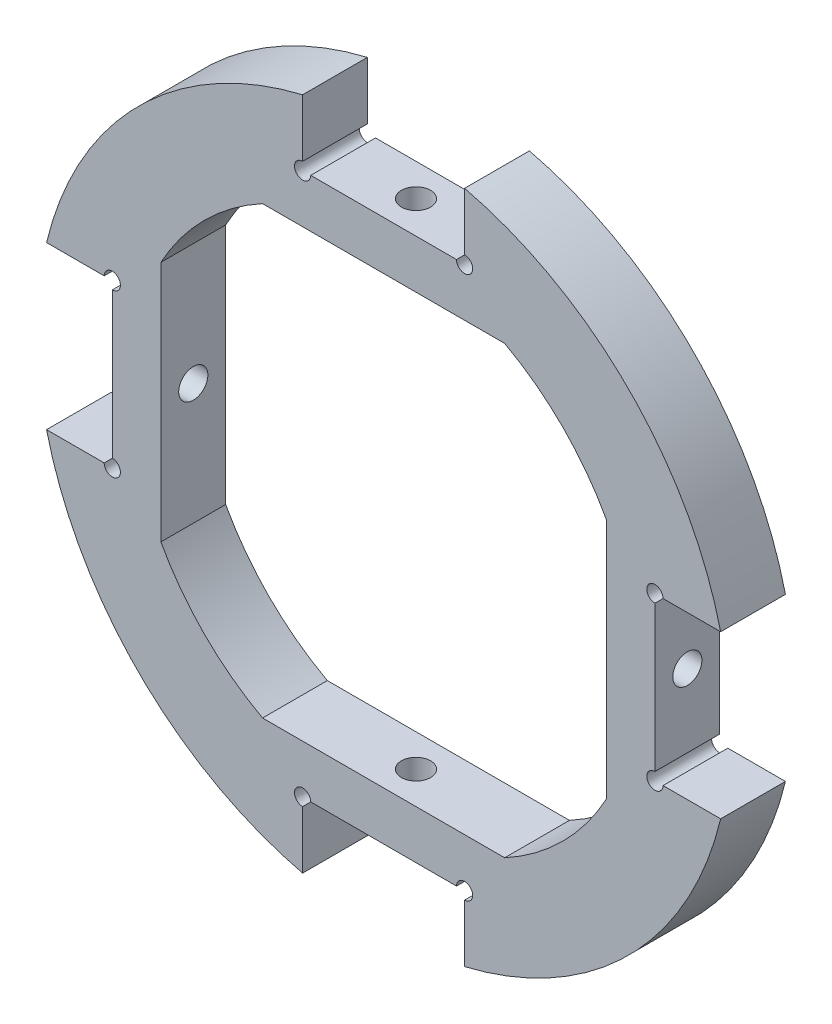
SolidWorks part; units mm, degrees
ref_plane "前视基准面" through (0, 0, 0) normal (0, 0, 1) x (1, 0, 0)
ref_plane "上视基准面" through (0, 0, 0) normal (0, 1, 0) x (1, 0, 0)
ref_plane "右视基准面" through (0, 0, 0) normal (1, 0, 0) x (0, 0, -1)
sketch "草图1" plane through (0, 0, 0) normal (0, 0, 1) x (1, 0, 0)
  line L0 (-24.4, 0) -> (24.4, 0) construction
  line L1 (-7.474, -13.75) -> (7.474, -13.75)
  line L2 (-7.474, 13.75) -> (7.474, 13.75)
  line L3 (13.75, 7.474) -> (13.75, -7.474)
  line L4 (-13.75, 7.474) -> (-13.75, -7.474)
  line L5 (-4.5, 16.75) -> (4.5, 16.75)
  line L6 (5, 20.8077) -> (5, 17.25)
  line L7 (-5, 20.8077) -> (-5, 17.25)
  line L8 (-16.75, -4.5) -> (-16.75, 4.5)
  line L9 (-20.8077, 5) -> (-17.25, 5)
  line L10 (-20.8077, -5) -> (-17.25, -5)
  line L11 (4.5, -16.75) -> (-4.5, -16.75)
  line L12 (-5, -20.8077) -> (-5, -17.25)
  line L13 (5, -20.8077) -> (5, -17.25)
  line L14 (16.75, 4.5) -> (16.75, -4.5)
  line L15 (20.8077, -5) -> (17.25, -5)
  line L16 (20.8077, 5) -> (17.25, 5)
  arc A0 (-7.474, 13.75) -> (-13.75, 7.474) centre (0, 0) ccw
  arc A1 (-13.75, -7.474) -> (-7.474, -13.75) centre (0, 0) ccw
  arc A2 (7.474, -13.75) -> (13.75, -7.474) centre (0, 0) ccw
  arc A3 (13.75, 7.474) -> (7.474, 13.75) centre (0, 0) ccw
  arc A4 (-5, 20.8077) -> (-20.8077, 5) centre (0, 0) ccw
  arc A5 (-20.8077, -5) -> (-5, -20.8077) centre (0, 0) ccw
  arc A6 (5, -20.8077) -> (20.8077, -5) centre (0, 0) ccw
  arc A7 (20.8077, 5) -> (5, 20.8077) centre (0, 0) ccw
  arc A8 (-5, 17.25) -> (-4.5, 16.75) centre (-5, 16.75) ccw
  arc A9 (4.5, 16.75) -> (5, 17.25) centre (5, 16.75) ccw
  arc A10 (-17.25, -5) -> (-16.75, -4.5) centre (-16.75, -5) ccw
  arc A11 (-16.75, 4.5) -> (-17.25, 5) centre (-16.75, 5) ccw
  arc A12 (5, -17.25) -> (4.5, -16.75) centre (5, -16.75) ccw
  arc A13 (-4.5, -16.75) -> (-5, -17.25) centre (-5, -16.75) ccw
  arc A14 (17.25, 5) -> (16.75, 4.5) centre (16.75, 5) ccw
  arc A15 (16.75, -4.5) -> (17.25, -5) centre (16.75, -5) ccw
extrude "凸台-拉伸1" add sketch "草图1" along normal blind 4
sketch "草图2" plane through (0, 16.75, 0) normal (0, 1, 0) x (1, 0, 0)
  line L0 (4.5, 0) -> (-4.5, 0) construction
  circle A0 centre (0, -2) radius 0.9
  dimension "D1" = 1.8
  dimension "D2" = 2
extrude "切除-拉伸1" cut sketch "草图2" against normal blind 43
pattern_circular "阵列(圆周)1" count 4 over 360 about axis through (0, 0, 4) along (0, 0, -1) of "切除-拉伸1"
